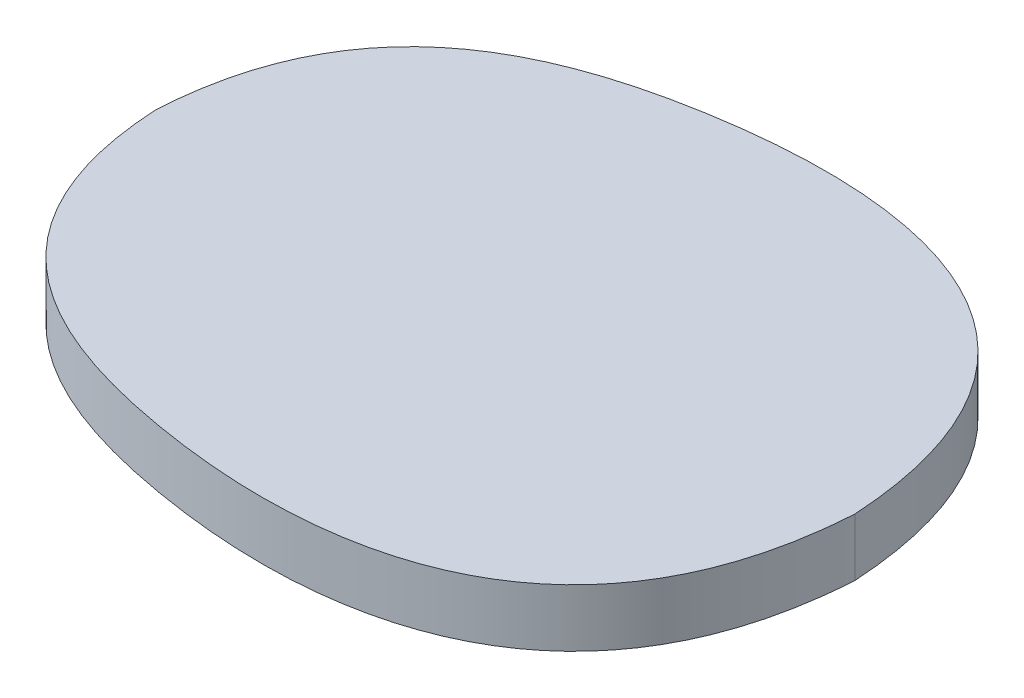
SolidWorks part; units mm, degrees
ref_plane "Front Plane" through (0, 0, 0) normal (0, 0, 1) x (1, 0, 0)
ref_plane "Top Plane" through (0, 0, 0) normal (0, 1, 0) x (1, 0, 0)
ref_plane "Right Plane" through (0, 0, 0) normal (1, 0, 0) x (0, 0, -1)
sketch "Sketch1" plane through (0, 0, 0) normal (0, 1, 0) x (1, 0, 0)
  spline S0 degree 3 poles (-50.8406, 0) (-49.0751, 32.4071) (2.4741, 57.3578) (67.7072, 46.9007) (70.5274, 0) knots 0 0 0 0 0.418326 1 1 1 1
  spline S1 degree 3 poles (-50.8406, 0) (-49.0751, -32.4071) (2.4741, -57.3578) (67.7072, -46.9007) (70.5274, 0) knots 0 0 0 0 0.418326 1 1 1 1
extrude "Extrude1" add sketch "Sketch1" along normal blind 10
